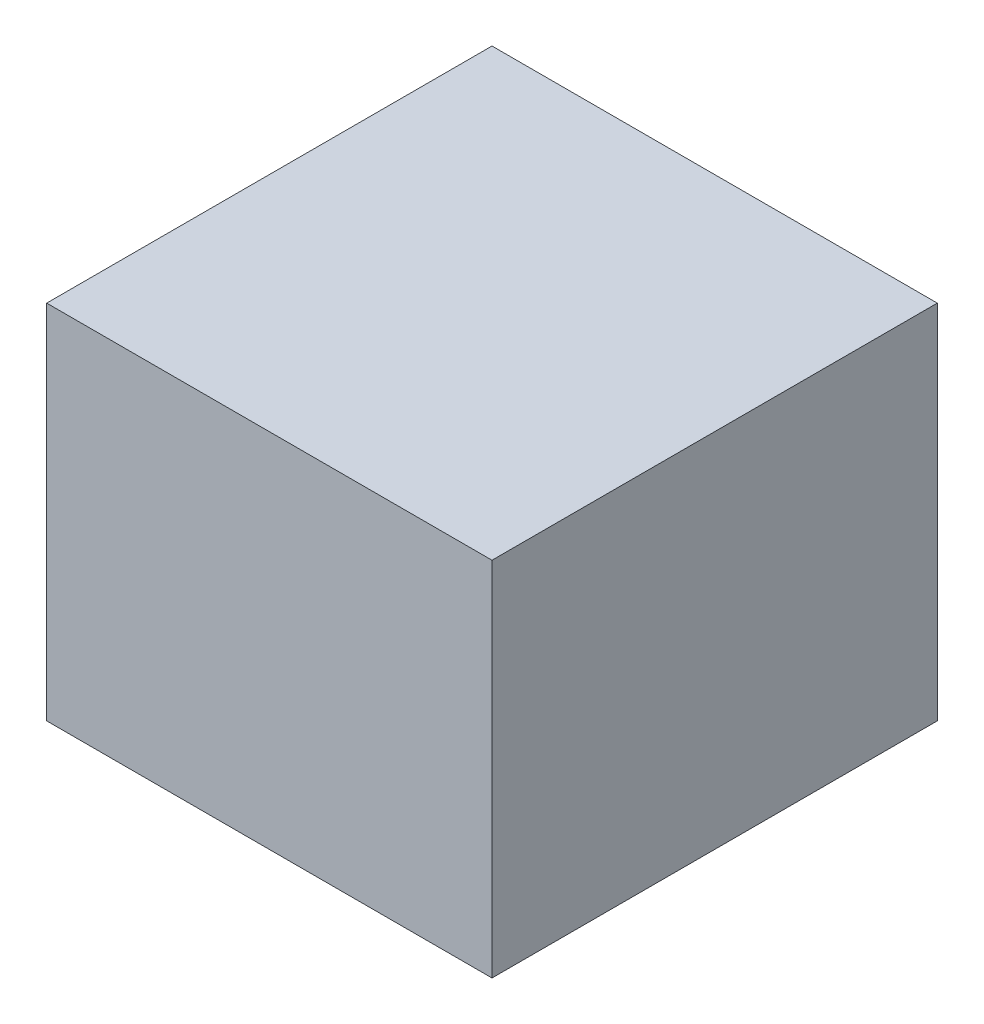
SolidWorks part; units mm, degrees
ref_plane "前视基准面" through (0, 0, 0) normal (0, 0, 1) x (1, 0, 0)
ref_plane "上视基准面" through (0, 0, 0) normal (0, 1, 0) x (1, 0, 0)
ref_plane "右视基准面" through (0, 0, 0) normal (1, 0, 0) x (0, 0, -1)
sketch "草图1" plane through (0, 0, 0) normal (0, 1, 0) x (1, 0, 0)
  line L1 (-80, 80) -> (80, 80)
  line L2 (-80, 80) -> (-80, -80)
  line L3 (-80, -80) -> (80, -80)
  line L4 (80, 80) -> (80, -80)
  line L5 (-80, 80) -> (80, -80) construction
  line L6 (-80, -80) -> (80, 80) construction
  point P0 (0, 0)
  dimension "D1" = 80
extrude "凸台-拉伸1" add sketch "草图1" along normal blind 100 and the other way blind 30
